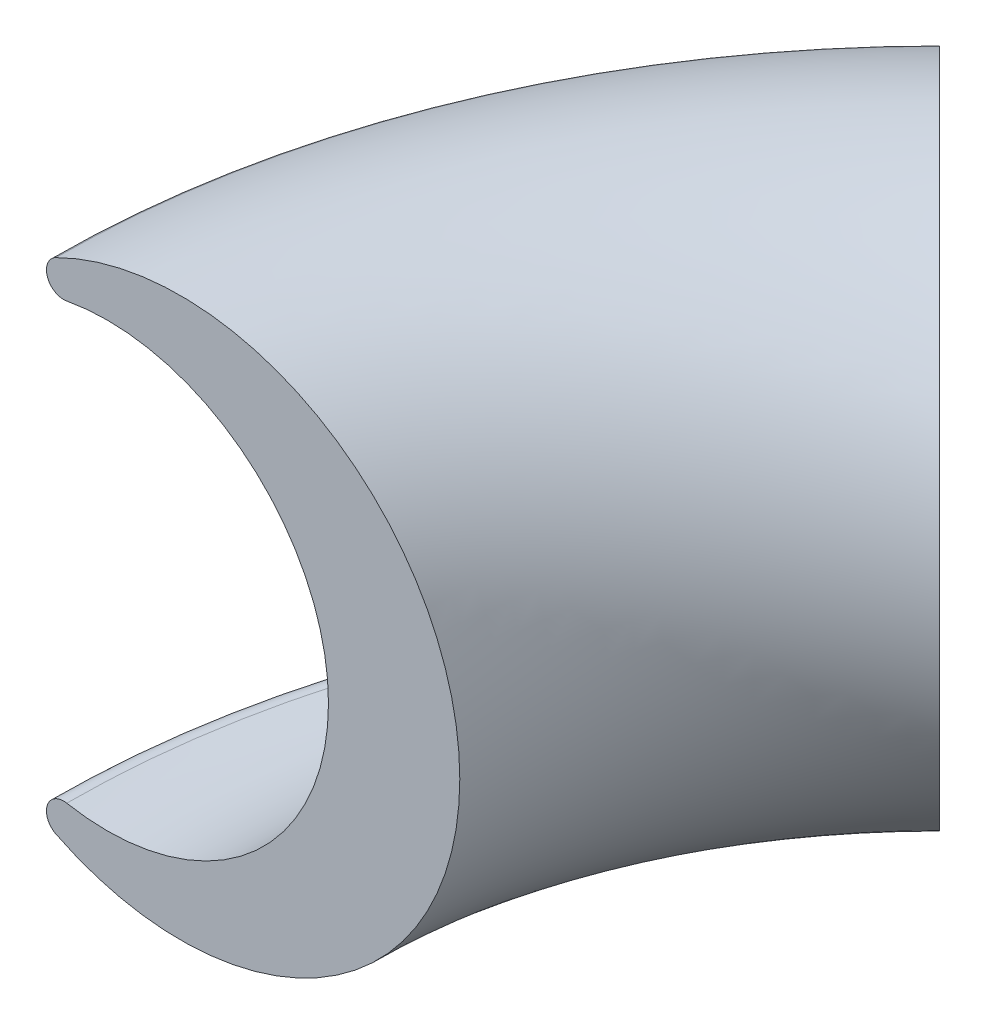
SolidWorks part; units mm, degrees
ref_plane "Front Plane" through (0, 0, 0) normal (0, 0, 1) x (1, 0, 0)
ref_plane "Top Plane" through (0, 0, 0) normal (0, 1, 0) x (1, 0, 0)
ref_plane "Right Plane" through (0, 0, 0) normal (1, 0, 0) x (0, 0, -1)
sketch "Sketch1" plane through (0, 0, 0) normal (0, 1, 0) x (1, 0, 0)
  line L0 (0, 0) -> (27.178, 0)
  line L1 (27.178, 0) -> (7.9603, 19.2177) construction
  arc A0 (0, 0) -> (7.9603, 19.2177) centre (27.178, 0) cw
  arc A1 (5.588, 0) -> (11.9116, 15.2664) centre (27.178, 0) cw
  arc A2 (0, 0) -> (54.356, 0) centre (27.178, 0) cw construction
  arc A3 (5.588, 0) -> (48.768, 0) centre (27.178, 0) cw construction
  arc A4 (11.176, 0) -> (15.8629, 11.3151) centre (27.178, 0) cw
  dimension "D2" = 27.178
  dimension "D1" = 45
  dimension "D3" = 5.588
  dimension "D4" = 11.176
sketch "Sketch2" plane through (0, 0, 0) normal (0, 0, 1) x (1, 0, 0)
  line L0 (27.178, 0) -> (5.588, 0)
  line L1 (5.588, 0) -> (1.6367, 3.9513) construction
  line L2 (0, 0) -> (27.178, 0) construction
  line L3 (5.4819, -0.1061) -> (5.3759, 0)
  line L4 (5.4819, 0.1061) -> (5.3759, 0)
  line L5 (5.4819, -0.1061) -> (1.4259, 3.9499) construction
  arc A0 (11.176, 0) -> (1.6367, 3.9513) centre (5.588, 0) ccw construction
  arc A1 (11.326, 0) -> (1.4259, 3.9499) centre (5.588, 0) ccw
  arc A2 (11.326, 0) -> (1.4259, -3.9499) centre (5.588, 0) cw
  arc A3 (1.4259, -3.9499) -> (1.4259, 3.9499) centre (7.493, 0) ccw
  dimension "D3" = 1.905
  dimension "D1" = 45
  dimension "D2" = 0.15
sweep "Sweep1" add profiles "Sketch2" path "Sketch1"
fillet "Fillet1" radius 0.4445 2 edges at (3.3862, 3.9499, -9.8549) (3.3862, -3.9499, -9.8549)
